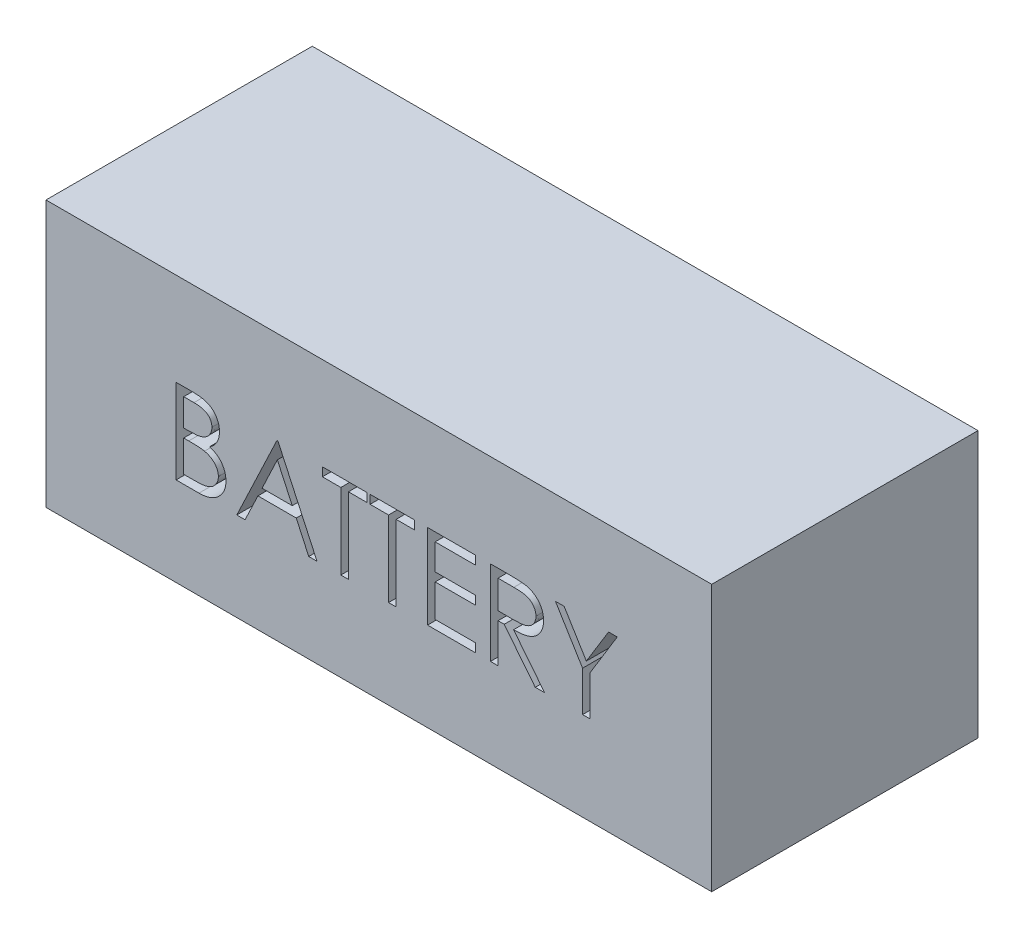
SolidWorks part; units mm, degrees
ref_plane "Front Plane" through (0, 0, 0) normal (0, 0, 1) x (1, 0, 0)
ref_plane "Top Plane" through (0, 0, 0) normal (0, 1, 0) x (1, 0, 0)
ref_plane "Right Plane" through (0, 0, 0) normal (1, 0, 0) x (0, 0, -1)
sketch "Sketch1" plane through (0, 0, 0) normal (1, 0, 0) x (0, 0, -1)
  line L1 (-30, 30) -> (30, 30)
  line L2 (-30, 30) -> (-30, -30)
  line L3 (-30, -30) -> (30, -30)
  line L4 (30, 30) -> (30, -30)
  point P4 (0, 30)
  point P5 (-30, 0)
  dimension "D1" = 60
  dimension "D2" = 60
extrude "Boss-Extrude1" add sketch "Sketch1" against normal mid plane 150 contours L2 L3 L4 L1
sketch "Sketch2" plane through (0, 0, 30) normal (0, 0, 1) x (1, 0, 0)
  text T0 "BATTERY" font "Century Gothic" height in points 72
extrude "Cut-Extrude1" cut sketch "Sketch2" against normal blind 10
